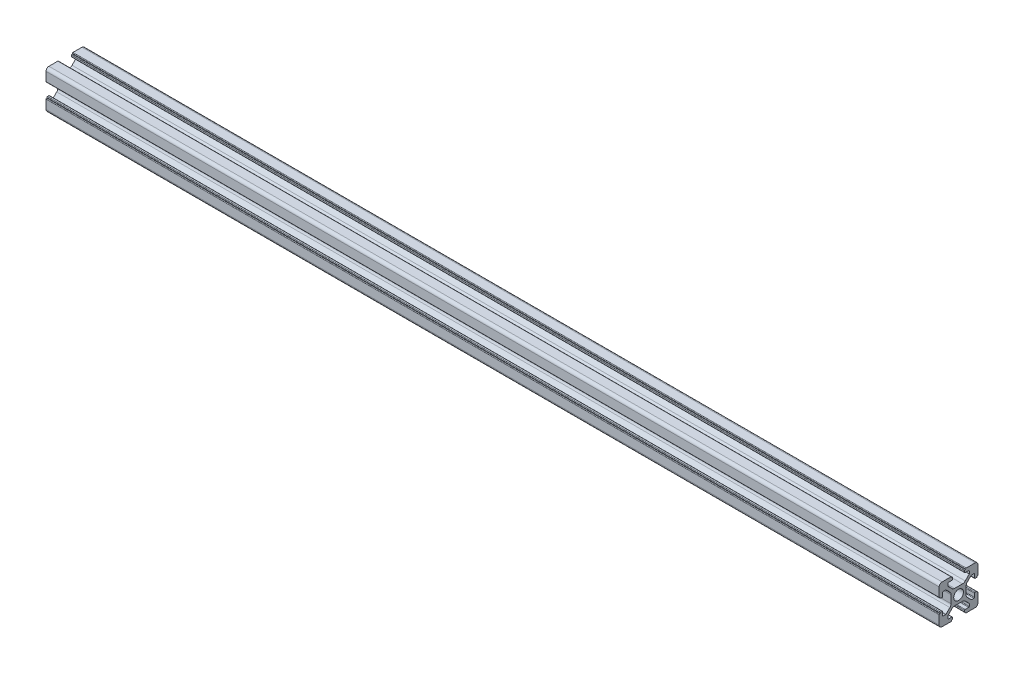
SolidWorks part; units mm, degrees
material "6061 Alloy"
ref_plane "Front Plane" through (0, 0, 0) normal (0, 0, 1) x (1, 0, 0)
ref_plane "Top Plane" through (0, 0, 0) normal (0, 1, 0) x (1, 0, 0)
ref_plane "Right Plane" through (0, 0, 0) normal (1, 0, 0) x (0, 0, -1)
sketch "Sketch1" plane through (0, 0, 0) normal (0, 0, 1) x (1, 0, 0)
  line L0 (-230, 0) -> (230, 0)
  dimension "D1" = 460
other "铝型材 2020(1)"
ref_plane "Plane1" through (-230, 0, 0) normal (1, 0, 0) x (0, 1, 0)
sketch "草图1" plane through (-230, 0, 0) normal (1, 0, 0) x (0, 1, 0)
  line L0 (3.9, 0) -> (3.9, -2.0109)
  line L1 (4.4858, -3.4251) -> (6.5607, -5.5)
  line L2 (6.5607, -5.5) -> (7.9, -5.5)
  line L3 (8.2, -5.2) -> (8.2, -3.4)
  line L4 (8.5, -3.1) -> (9.2, -3.1)
  line L5 (9.5, -3.4) -> (9.5, -3.6)
  line L6 (9.5, -3.6) -> (9.7, -3.6)
  line L7 (10, -3.9) -> (10, -8.5)
  line L8 (8.5, -10) -> (3.9, -10)
  line L9 (3.1, -9.2) -> (3.1, -8.5)
  line L10 (3.4, -8.2) -> (5.2, -8.2)
  line L11 (5.5, -7.9) -> (5.5, -6.6849)
  line L12 (5.4121, -6.4728) -> (3.4251, -4.4858)
  line L13 (2.0109, -3.9) -> (0, -3.9)
  line L14 (0, -3.9) -> (-2.0109, -3.9)
  line L15 (-3.4251, -4.4858) -> (-5.4121, -6.4728)
  line L16 (-5.5, -6.6849) -> (-5.5, -7.9)
  line L17 (-5.2, -8.2) -> (-3.4, -8.2)
  line L18 (-3.1, -8.5) -> (-3.1, -9.2)
  line L19 (-3.9, -10) -> (-8.5, -10)
  line L20 (-10, -8.5) -> (-10, -3.9)
  line L21 (-9.7, -3.6) -> (-9.5, -3.6)
  line L22 (-9.5, -3.6) -> (-9.5, -3.4)
  line L23 (-9.2, -3.1) -> (-8.5, -3.1)
  line L24 (-8.2, -3.4) -> (-8.2, -5.2)
  line L25 (-7.9, -5.5) -> (-6.6849, -5.5)
  line L26 (-6.4728, -5.4121) -> (-4.4858, -3.4251)
  line L27 (-3.9, -2.0109) -> (-3.9, 0)
  line L28 (-3.9, 0) -> (-3.9, 2.0109)
  line L29 (-4.4858, 3.4251) -> (-6.4728, 5.4121)
  line L30 (-6.6849, 5.5) -> (-7.9, 5.5)
  line L31 (-8.2, 5.2) -> (-8.2, 3.4)
  line L32 (-8.5, 3.1) -> (-9.2, 3.1)
  line L33 (-9.5, 3.4) -> (-9.5, 3.6)
  line L34 (-9.5, 3.6) -> (-9.7, 3.6)
  line L35 (-10, 3.9) -> (-10, 8.5)
  line L36 (-8.5, 10) -> (-3.9, 10)
  line L37 (-3.6, 9.7) -> (-3.6, 9.5)
  line L38 (-3.6, 9.5) -> (-3.4, 9.5)
  line L39 (-3.1, 9.2) -> (-3.1, 8.5)
  line L40 (-3.4, 8.2) -> (-5.2, 8.2)
  line L41 (-5.5, 7.9) -> (-5.5, 6.6849)
  line L42 (-5.4121, 6.4728) -> (-3.4251, 4.4858)
  line L43 (-2.0109, 3.9) -> (0, 3.9)
  line L44 (0, 3.9) -> (2.0109, 3.9)
  line L45 (3.4251, 4.4858) -> (5.4121, 6.4728)
  line L46 (5.5, 6.6849) -> (5.5, 7.9)
  line L47 (5.2, 8.2) -> (3.4, 8.2)
  line L48 (3.1, 8.5) -> (3.1, 9.2)
  line L49 (3.4, 9.5) -> (3.6, 9.5)
  line L50 (3.6, 9.5) -> (3.6, 9.7)
  line L51 (3.9, 10) -> (8.5, 10)
  line L52 (10, 8.5) -> (10, 3.9)
  line L53 (9.7, 3.6) -> (9.5, 3.6)
  line L54 (9.5, 3.6) -> (9.5, 3.4)
  line L55 (9.2, 3.1) -> (8.5, 3.1)
  line L56 (8.2, 3.4) -> (8.2, 5.2)
  line L57 (7.9, 5.5) -> (6.6849, 5.5)
  line L58 (6.4728, 5.4121) -> (4.4858, 3.4251)
  line L59 (3.9, 2.0109) -> (3.9, 0)
  circle A0 centre (0, 0) radius 2.5
  arc A1 (3.9, -2.0109) -> (4.4858, -3.4251) centre (5.9, -2.0109) ccw
  arc A2 (7.9, -5.5) -> (8.2, -5.2) centre (7.9, -5.2) ccw
  arc A3 (8.5, -3.1) -> (8.2, -3.4) centre (8.5, -3.4) ccw
  arc A4 (9.5, -3.4) -> (9.2, -3.1) centre (9.2, -3.4) ccw
  arc A5 (10, -3.9) -> (9.7, -3.6) centre (9.7, -3.9) ccw
  arc A6 (8.5, -10) -> (10, -8.5) centre (8.5, -8.5) ccw
  arc A7 (3.6, -9.7) -> (3.9, -10) centre (3.9, -9.7) ccw
  arc A8 (3.6, -9.7) -> (3.4, -9.5) centre (3.4, -9.7) ccw
  arc A9 (3.1, -9.2) -> (3.4, -9.5) centre (3.4, -9.2) ccw
  arc A10 (3.4, -8.2) -> (3.1, -8.5) centre (3.4, -8.5) ccw
  arc A11 (5.2, -8.2) -> (5.5, -7.9) centre (5.2, -7.9) ccw
  arc A12 (5.5, -6.6849) -> (5.4121, -6.4728) centre (5.2, -6.6849) ccw
  arc A13 (3.4251, -4.4858) -> (2.0109, -3.9) centre (2.0109, -5.9) ccw
  arc A14 (-2.0109, -3.9) -> (-3.4251, -4.4858) centre (-2.0109, -5.9) ccw
  arc A15 (-5.4121, -6.4728) -> (-5.5, -6.6849) centre (-5.2, -6.6849) ccw
  arc A16 (-5.5, -7.9) -> (-5.2, -8.2) centre (-5.2, -7.9) ccw
  arc A17 (-3.1, -8.5) -> (-3.4, -8.2) centre (-3.4, -8.5) ccw
  arc A18 (-3.4, -9.5) -> (-3.1, -9.2) centre (-3.4, -9.2) ccw
  arc A19 (-3.4, -9.5) -> (-3.6, -9.7) centre (-3.4, -9.7) ccw
  arc A20 (-3.9, -10) -> (-3.6, -9.7) centre (-3.9, -9.7) ccw
  arc A21 (-10, -8.5) -> (-8.5, -10) centre (-8.5, -8.5) ccw
  arc A22 (-9.7, -3.6) -> (-10, -3.9) centre (-9.7, -3.9) ccw
  arc A23 (-9.2, -3.1) -> (-9.5, -3.4) centre (-9.2, -3.4) ccw
  arc A24 (-8.2, -3.4) -> (-8.5, -3.1) centre (-8.5, -3.4) ccw
  arc A25 (-8.2, -5.2) -> (-7.9, -5.5) centre (-7.9, -5.2) ccw
  arc A26 (-6.6849, -5.5) -> (-6.4728, -5.4121) centre (-6.6849, -5.2) ccw
  arc A27 (-4.4858, -3.4251) -> (-3.9, -2.0109) centre (-5.9, -2.0109) ccw
  arc A28 (-3.9, 2.0109) -> (-4.4858, 3.4251) centre (-5.9, 2.0109) ccw
  arc A29 (-6.4728, 5.4121) -> (-6.6849, 5.5) centre (-6.6849, 5.2) ccw
  arc A30 (-7.9, 5.5) -> (-8.2, 5.2) centre (-7.9, 5.2) ccw
  arc A31 (-8.5, 3.1) -> (-8.2, 3.4) centre (-8.5, 3.4) ccw
  arc A32 (-9.5, 3.4) -> (-9.2, 3.1) centre (-9.2, 3.4) ccw
  arc A33 (-10, 3.9) -> (-9.7, 3.6) centre (-9.7, 3.9) ccw
  arc A34 (-8.5, 10) -> (-10, 8.5) centre (-8.5, 8.5) ccw
  arc A35 (-3.6, 9.7) -> (-3.9, 10) centre (-3.9, 9.7) ccw
  arc A36 (-3.1, 9.2) -> (-3.4, 9.5) centre (-3.4, 9.2) ccw
  arc A37 (-3.4, 8.2) -> (-3.1, 8.5) centre (-3.4, 8.5) ccw
  arc A38 (-5.2, 8.2) -> (-5.5, 7.9) centre (-5.2, 7.9) ccw
  arc A39 (-5.5, 6.6849) -> (-5.4121, 6.4728) centre (-5.2, 6.6849) ccw
  arc A40 (-3.4251, 4.4858) -> (-2.0109, 3.9) centre (-2.0109, 5.9) ccw
  arc A41 (2.0109, 3.9) -> (3.4251, 4.4858) centre (2.0109, 5.9) ccw
  arc A42 (5.4121, 6.4728) -> (5.5, 6.6849) centre (5.2, 6.6849) ccw
  arc A43 (5.5, 7.9) -> (5.2, 8.2) centre (5.2, 7.9) ccw
  arc A44 (3.1, 8.5) -> (3.4, 8.2) centre (3.4, 8.5) ccw
  arc A45 (3.4, 9.5) -> (3.1, 9.2) centre (3.4, 9.2) ccw
  arc A46 (3.9, 10) -> (3.6, 9.7) centre (3.9, 9.7) ccw
  arc A47 (10, 8.5) -> (8.5, 10) centre (8.5, 8.5) ccw
  arc A48 (9.7, 3.6) -> (10, 3.9) centre (9.7, 3.9) ccw
  arc A49 (9.2, 3.1) -> (9.5, 3.4) centre (9.2, 3.4) ccw
  arc A50 (8.2, 3.4) -> (8.5, 3.1) centre (8.5, 3.4) ccw
  arc A51 (8.2, 5.2) -> (7.9, 5.5) centre (7.9, 5.2) ccw
  arc A52 (6.6849, 5.5) -> (6.4728, 5.4121) centre (6.6849, 5.2) ccw
  arc A53 (4.4858, 3.4251) -> (3.9, 2.0109) centre (5.9, 2.0109) ccw
  point P0 (-10, 10)
  point P1 (10, 10)
  point P2 (10, -10)
  point P171 (-10, -10)
  point P172 (-10, 0)
  point P173 (10, 0)
  point P174 (0, -10)
  point P175 (0, 10)
  point P176 (0, 0)
  point P177 (0, 0)
